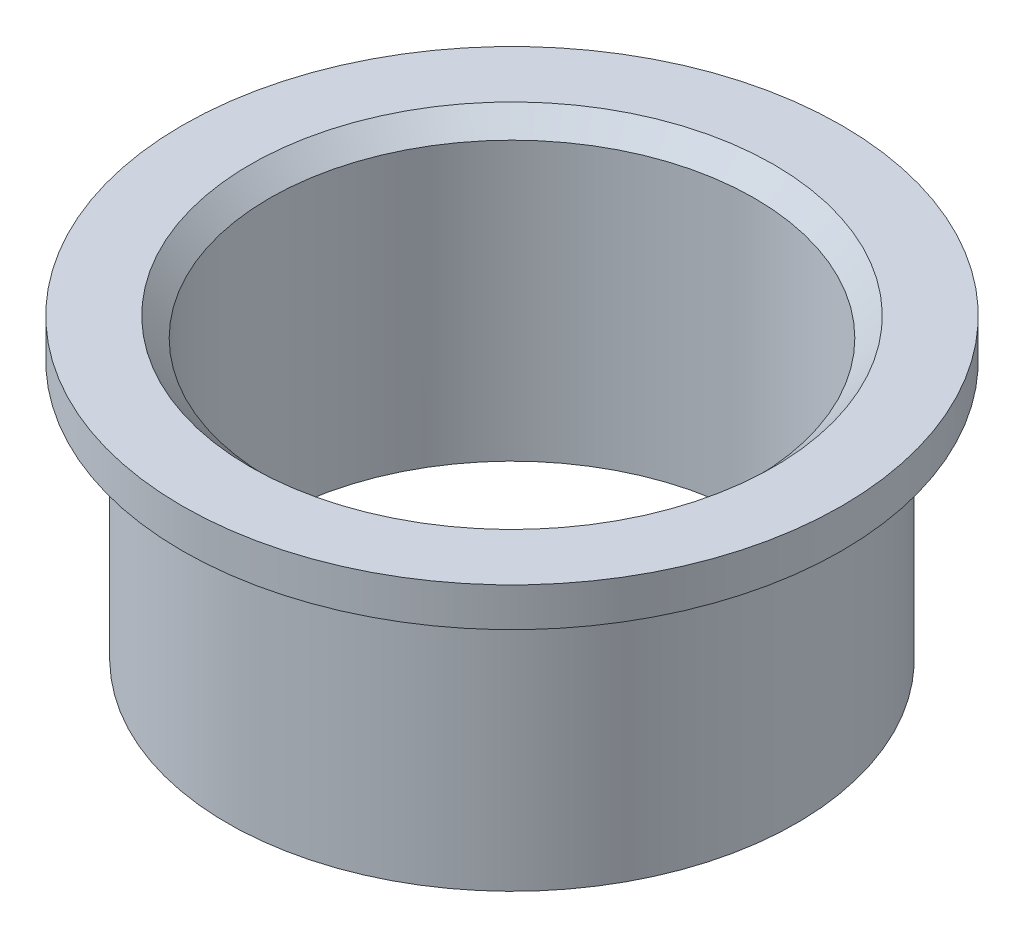
SolidWorks part; units mm, degrees
ref_plane "Front Plane" through (0, 0, 0) normal (0, 0, 1) x (1, 0, 0)
ref_plane "Top Plane" through (0, 0, 0) normal (0, 1, 0) x (1, 0, 0)
ref_plane "Right Plane" through (0, 0, 0) normal (1, 0, 0) x (0, 0, -1)
sketch "Sketch1" plane through (0, 0, 0) normal (0, 0, 1) x (1, 0, 0)
  line L6 (37.5, 0) -> (37.5, 46)
  line L7 (37.5, 46) -> (51, 46)
  line L8 (51, 46) -> (51, 40)
  line L9 (51, 40) -> (44, 40)
  line L10 (44, 40) -> (44, 0)
  line L11 (44, 0) -> (37.5, 0)
  line L12 (0, 0) -> (0, 82.2477) construction
  dimension "D1" = 37.5
  dimension "D2" = 44
  dimension "D3" = 51
  dimension "D4" = 6
  dimension "D5" = 40
revolve "Revolve1" add sketch "Sketch1" angle 360 about L12
chamfer "Chamfer1" distance 3 angle 45 1 edges at (0, 46, -37.5)
